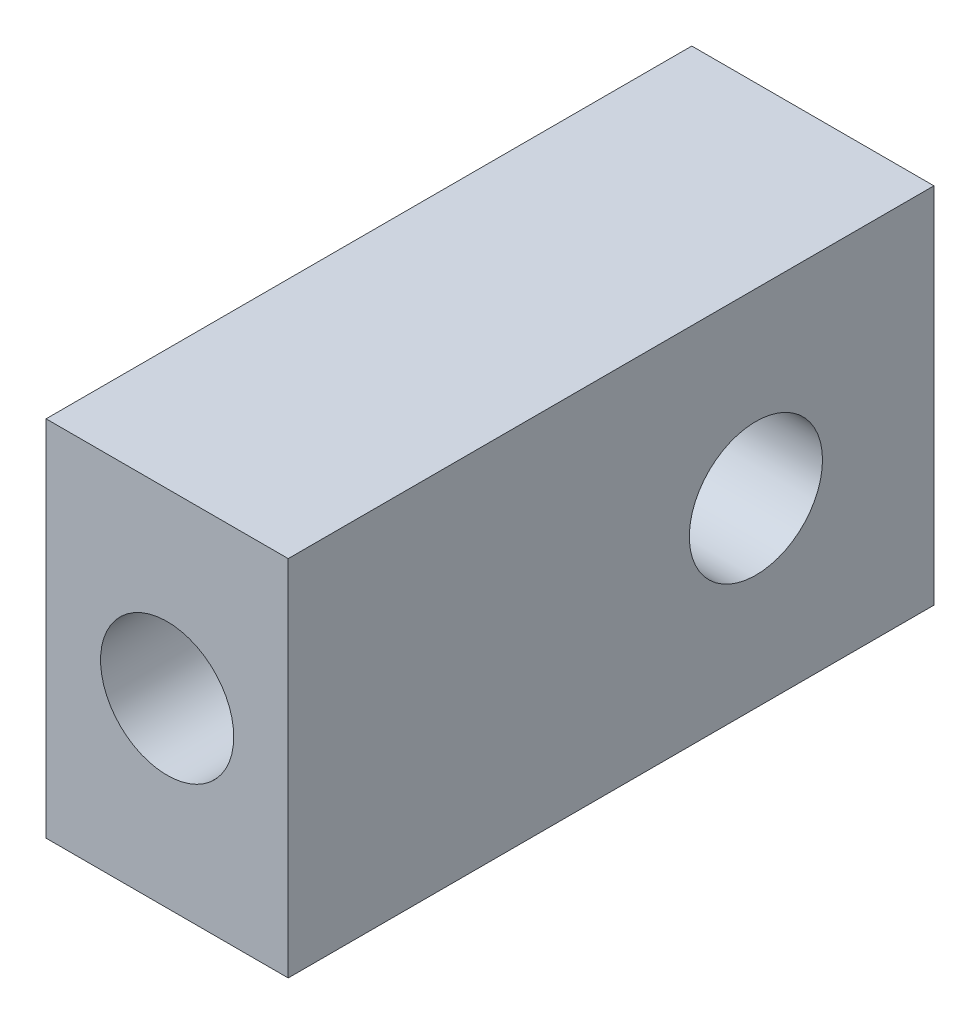
SolidWorks part; units mm, degrees
material "6061 Alloy"
ref_plane "Front Plane" through (0, 0, 0) normal (0, 0, 1) x (1, 0, 0)
ref_plane "Top Plane" through (0, 0, 0) normal (0, 1, 0) x (1, 0, 0)
ref_plane "Right Plane" through (0, 0, 0) normal (1, 0, 0) x (0, 0, -1)
sketch "Sketch1" plane through (0, 0, 0) normal (0, 0, 1) x (1, 0, 0)
  line L1 (-3, -4.5) -> (3, -4.5)
  line L2 (-3, -4.5) -> (-3, 4.5)
  line L3 (-3, 4.5) -> (3, 4.5)
  line L4 (3, -4.5) -> (3, 4.5)
  line L5 (-3, -4.5) -> (3, 4.5) construction
  line L6 (-3, 4.5) -> (3, -4.5) construction
  point P0 (0, 0)
  dimension "D1" = 9
  dimension "D2" = 6
extrude "Boss-Extrude1" add sketch "Sketch1" along normal blind 16
sketch "Sketch2" plane through (0, 0, 16) normal (0, 0, 1) x (1, 0, 0)
  point P0 (0, 0)
hole_wizard "M4 Tapped Hole1" positions "Sketch3" profile "Sketch4" tap size "M4" standard "ISO"
sketch "Sketch3" plane through (0, 0, 16) normal (0, 0, 1) x (1, 0, 0)
  point P0 (0, 0)
sketch "Sketch4" plane through (0, 0, 16) normal (1, 0, 0) x (0, -1, 0)
  line L0 (0, 0) -> (0, 6.9914)
  line L1 (0, 6.9914) -> (1.65, 6)
  line L2 (1.65, 6) -> (1.65, 0)
  line L5 (1.65, 0) -> (0, 0)
  line L10 (0, 6.9914) -> (-1.65, 6) construction
  line L11 (0, -6.35) -> (0, 107.95) construction
  dimension "Tap Drill Dia." = 3.3
  dimension "Tap Drill Depth" = 6
  dimension "Drill Angle" = 118
cosmetic thread "Hole Thread1" parameters "D1"=6, "D2"=4
sketch "Sketch5" plane through (0, 0, 0) normal (0, 0, -1) x (-1, 0, 0)
  line L0 (3, -4.5) -> (-3, -4.5) construction
  line L1 (3, 4.5) -> (0, 4.5)
  line L2 (3, 4.5) -> (3, -4.5)
  line L3 (3, -4.5) -> (0, -4.5)
  line L4 (0, 4.5) -> (0, -4.5)
extrude "Cut-Extrude1" [suppressed] cut sketch "Sketch5" against normal blind 8
sketch "Sketch6" plane through (3, 0, 0) normal (1, 0, 0) x (0, 0, -1)
  line L0 (0, -4.5) -> (0, 4.5) construction
  circle A0 centre (-3, 0) radius 1.5
  dimension "D1" = 3
  dimension "D2" = 3
extrude "Cut-Extrude2" [suppressed] cut sketch "Sketch6" against normal up to surface (3 mm away)
hole_wizard "M4 Tapped Hole2" positions "Sketch8" profile "Sketch9" tap size "M4" standard "ISO" end condition through all
sketch "Sketch8" plane through (3, 0, 0) normal (1, 0, 0) x (0, 0, -1)
  line L0 (0, -4.5) -> (0, 4.5) construction
  line L1 (-4.4111, 0) -> (0, 0) construction
  point P0 (-4.4111, 0)
sketch "Sketch9" plane through (3, 0, 4.4111) normal (0, 1, 0) x (0, 0, -1)
  line L0 (0, 0) -> (0, 6)
  line L1 (0, 6) -> (1.65, 6)
  line L2 (1.65, 6) -> (1.65, 0)
  line L5 (1.65, 0) -> (0, 0)
  line L11 (0, -6.35) -> (0, 107.95) construction
  dimension "Thru Tap Drill Dia." = 3.3
  dimension "Thru Tap Drill Depth" = 6
cosmetic thread "Hole Thread2" parameters "D2"=4
